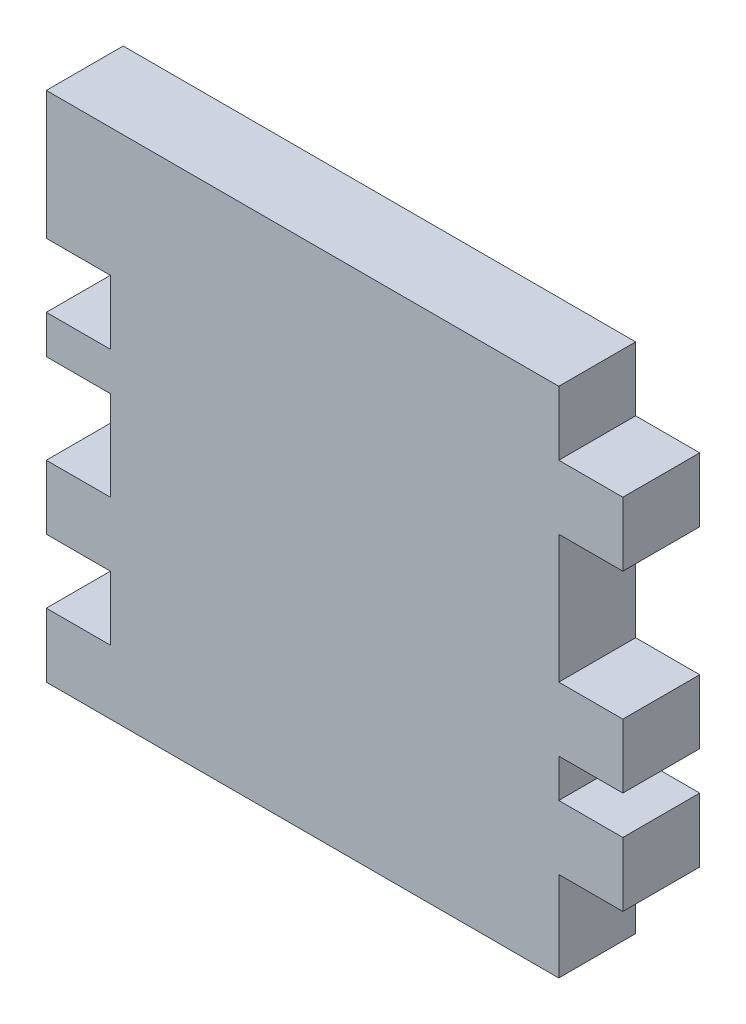
SolidWorks part; units mm, degrees
ref_plane "Front Plane" through (0, 0, 0) normal (0, 0, 1) x (1, 0, 0)
ref_plane "Top Plane" through (0, 0, 0) normal (0, 1, 0) x (1, 0, 0)
ref_plane "Right Plane" through (0, 0, 0) normal (1, 0, 0) x (0, 0, -1)
sketch "Sketch1" plane through (0, 0, 0) normal (0, 0, 1) x (1, 0, 0)
  line L1 (-21.2611, 17.3845) -> (23.7389, 17.3845)
  line L2 (-21.2611, 17.3845) -> (-21.2611, -22.6155)
  line L3 (-21.2611, -22.6155) -> (23.7389, -22.6155)
  line L4 (23.7389, 17.3845) -> (23.7389, -22.6155)
  dimension "D1" = 45
  dimension "D2" = 40
extrude "Boss-Extrude1" add sketch "Sketch1" along normal blind 6 contours L2 L1 L4 L3
sketch "Sketch2" plane through (0, 0, 6) normal (0, 0, 1) x (1, 0, 0)
  line L0 (-21.2611, 17.3845) -> (-21.2611, -22.6155) construction
  line L1 (-21.2611, 7.3845) -> (-16.2611, 7.3845)
  line L2 (-21.2611, 7.3845) -> (-21.2611, 2.3845)
  line L3 (-21.2611, 2.3845) -> (-16.2611, 2.3845)
  line L4 (-16.2611, 7.3845) -> (-16.2611, 2.3845)
  line L5 (-21.2611, 17.3845) -> (23.7389, 17.3845) construction
  line L6 (-21.2611, -0.6155) -> (-16.2611, -0.6155)
  line L7 (-21.2611, -0.6155) -> (-21.2611, -7.6155)
  line L8 (-21.2611, -7.6155) -> (-16.2611, -7.6155)
  line L9 (-16.2611, -0.6155) -> (-16.2611, -7.6155)
  line L10 (-21.2611, -12.6155) -> (-16.2611, -12.6155)
  line L11 (-21.2611, -12.6155) -> (-21.2611, -17.6155)
  line L12 (-21.2611, -17.6155) -> (-16.2611, -17.6155)
  line L13 (-16.2611, -12.6155) -> (-16.2611, -17.6155)
  dimension "D1" = 5
  dimension "D2" = 10
  dimension "D3" = 7
  dimension "D4" = 3
  dimension "D5" = 5
  dimension "D6" = 5
  dimension "D7" = 5
  dimension "D8" = 5
  dimension "D9" = 5
extrude "Cut-Extrude1" cut sketch "Sketch2" against normal blind 6 contours L2 L1 L4 L3 | L7 L6 L9 L8 | L11 L10 L13 L12
sketch "Sketch3" plane through (0, 0, 6) normal (0, 0, 1) x (1, 0, 0)
  line L0 (23.7389, 17.3845) -> (23.7389, -22.6155) construction
  line L1 (23.7389, -17.6155) -> (18.7389, -17.6155)
  line L2 (23.7389, -17.6155) -> (23.7389, -22.6155)
  line L3 (23.7389, -22.6155) -> (18.7389, -22.6155)
  line L4 (18.7389, -17.6155) -> (18.7389, -22.6155)
  line L5 (-21.2611, -22.6155) -> (23.7389, -22.6155) construction
  line L6 (-21.2611, 17.3845) -> (23.7389, 17.3845) construction
  line L7 (23.7389, -7.6155) -> (18.7389, -7.6155)
  line L8 (23.7389, -7.6155) -> (23.7389, -10.6155)
  line L9 (23.7389, -10.6155) -> (18.7389, -10.6155)
  line L10 (18.7389, -7.6155) -> (18.7389, -10.6155)
  line L15 (23.7389, 12.3845) -> (18.7389, 12.3845)
  line L16 (23.7389, 12.3845) -> (23.7389, 17.3845)
  line L17 (23.7389, 17.3845) -> (18.7389, 17.3845)
  line L18 (18.7389, 12.3845) -> (18.7389, 17.3845)
  line L20 (23.7389, 7.3845) -> (18.7389, 7.3845)
  line L21 (23.7389, 7.3845) -> (23.7389, -2.6155)
  line L22 (23.7389, -2.6155) -> (18.7389, -2.6155)
  line L23 (18.7389, 7.3845) -> (18.7389, -2.6155)
  dimension "D1" = 5
  dimension "D2" = 5
  dimension "D3" = 5
  dimension "D4" = 10
  dimension "D5" = 5
  dimension "D6" = 3
  dimension "D7" = 7
extrude "Cut-Extrude2" cut sketch "Sketch3" against normal blind 6 contours L16 L15 L18 L17 | L21 L20 L23 L22 | L8 L7 L10 L9 | L2 L1 L4 L3
sketch "Sketch4" plane through (0, 0, 6) normal (0, 0, 1) x (1, 0, 0)
  line L0 (23.7389, -10.6155) -> (23.7389, -17.6155) construction
  line L1 (18.7389, -22.6155) -> (23.7389, -22.6155)
  line L2 (18.7389, -22.6155) -> (18.7389, -15.6155)
  line L3 (18.7389, -15.6155) -> (23.7389, -15.6155)
  line L4 (23.7389, -22.6155) -> (23.7389, -15.6155)
  dimension "D1" = 7
extrude "Cut-Extrude3" cut sketch "Sketch4" against normal blind 6 contours L2 L1 L4 L3
